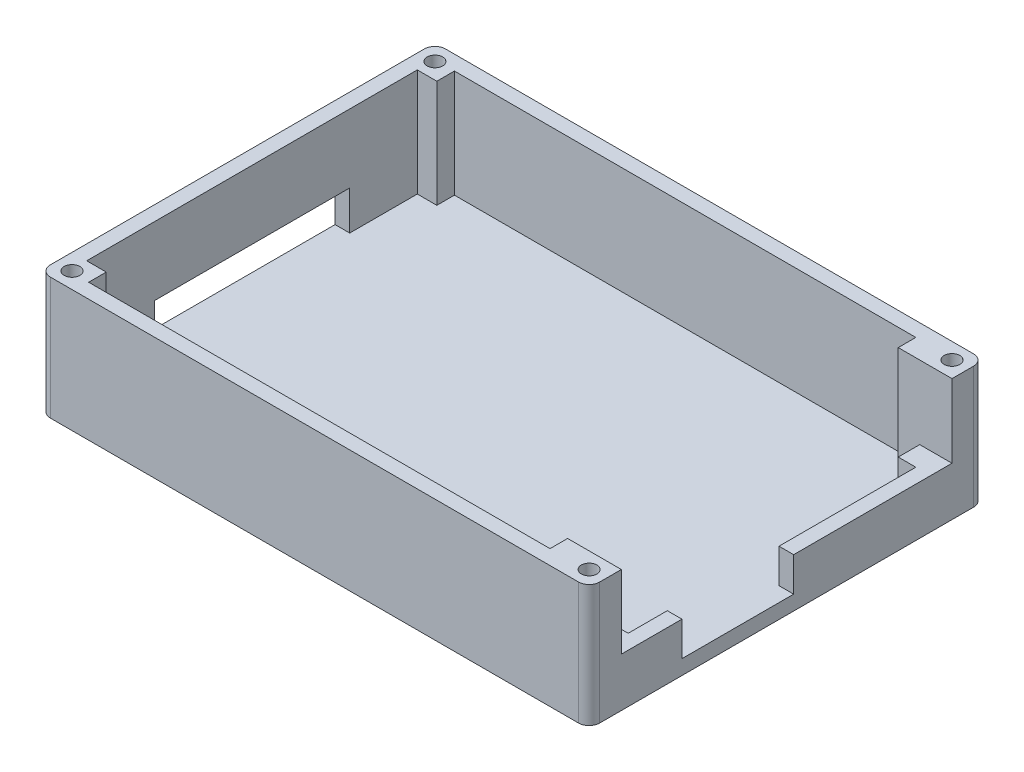
SolidWorks part; units mm, degrees
ref_plane "前视基准面" through (0, 0, 0) normal (0, 0, 1) x (1, 0, 0)
ref_plane "上视基准面" through (0, 0, 0) normal (0, 1, 0) x (1, 0, 0)
ref_plane "右视基准面" through (0, 0, 0) normal (1, 0, 0) x (0, 0, -1)
sketch "草图1" plane through (0, 0, 0) normal (0, 1, 0) x (1, 0, 0)
  line L1 (-38.8758, 22.2147) -> (17.3342, 22.2147)
  line L2 (-38.8758, 22.2147) -> (-38.8758, -18.2153)
  line L3 (-38.8758, -18.2153) -> (17.3342, -18.2153)
  line L4 (17.3342, 22.2147) -> (17.3342, -18.2153)
  line L5 (-10.7708, -18.2153) -> (-10.7708, 22.2147) construction
  line L6 (-38.8758, 1.9997) -> (17.3342, 1.9997) construction
  point P68 (-10.7708, 1.9997)
  dimension "D1" = 56.21
  dimension "D2" = 40.43
extrude "凸台-拉伸1" add sketch "草图1" along normal blind 1.5
sketch "草图2" plane through (0, 1.5, 0) normal (0, 1, 0) x (1, 0, 0)
  line L0 (-38.8758, -18.2153) -> (17.3342, -18.2153) construction
  line L1 (-38.8758, 22.2147) -> (-37.3758, 22.2147)
  line L2 (-38.8758, 22.2147) -> (-38.8758, -18.2153)
  line L3 (-38.8758, -18.2153) -> (-37.3758, -18.2153)
  line L4 (-37.3758, 22.2147) -> (-37.3758, -18.2153)
  line L5 (-38.1258, -18.2153) -> (-38.1258, 22.2147) construction
  line L6 (-38.8758, 1.9997) -> (-37.3758, 1.9997) construction
  line L7 (17.3342, -18.2153) -> (17.3342, 22.2147) construction
  line L12 (-37.3758, -18.2153) -> (17.3342, -18.2153)
  line L13 (-37.3758, -18.2153) -> (-37.3758, -16.7153)
  line L14 (-37.3758, -16.7153) -> (17.3342, -16.7153)
  line L15 (17.3342, -18.2153) -> (17.3342, -16.7153)
  line L16 (-10.0208, -16.7153) -> (-10.0208, -18.2153) construction
  line L17 (-37.3758, -17.4653) -> (17.3342, -17.4653) construction
  line L19 (-37.3758, 22.2147) -> (17.3342, 22.2147)
  line L20 (-37.3758, 22.2147) -> (-37.3758, 20.7147)
  line L21 (-37.3758, 20.7147) -> (17.3342, 20.7147)
  line L22 (17.3342, 22.2147) -> (17.3342, 20.7147)
  line L23 (-10.0208, 20.7147) -> (-10.0208, 22.2147) construction
  line L24 (-37.3758, 21.4647) -> (17.3342, 21.4647) construction
  point P152 (-38.1258, 1.9997)
  point P161 (-10.0208, 21.4647)
  point P193 (-10.0208, -17.4653)
  line M6 (-38.8758, 22.2147) -> (-38.8758, -18.2153)
  line M7 (-38.8758, -18.2153) -> (17.3342, -18.2153)
  line M8 (17.3342, -18.2153) -> (17.3342, 22.2147)
  line M9 (17.3342, 22.2147) -> (-38.8758, 22.2147)
  dimension "D1" = 1.5
  dimension "D2" = 1.5
  dimension "D3" = 1.5
extrude "凸台-拉伸2" add sketch "草图2" along normal blind 3.5 contours L4 M9 M6 M7 | L4 L21 M8 M9 | L14 L4 M7 M8
sketch "草图3" plane through (0, 1.5, 0) normal (0, 1, 0) x (1, 0, 0)
  line L1 (17.3342, -16.7153) -> (15.8342, -16.7153)
  line L2 (17.3342, -16.7153) -> (17.3342, -8.7153)
  line L3 (17.3342, -8.7153) -> (15.8342, -8.7153)
  line L4 (15.8342, -16.7153) -> (15.8342, -8.7153)
  line L5 (16.5842, -8.7153) -> (16.5842, -16.7153) construction
  line L6 (17.3342, -12.7153) -> (15.8342, -12.7153) construction
  line L7 (17.3342, 20.7147) -> (15.8342, 20.7147)
  line L8 (17.3342, 20.7147) -> (17.3342, 2.7147)
  line L9 (17.3342, 2.7147) -> (15.8342, 2.7147)
  line L10 (15.8342, 20.7147) -> (15.8342, 2.7147)
  line L11 (16.5842, 2.7147) -> (16.5842, 20.7147) construction
  line L12 (17.3342, 11.7147) -> (15.8342, 11.7147) construction
  point P108 (16.5842, 11.7147)
  point P172 (16.5842, -12.7153)
  dimension "D1" = 1.5
  dimension "D2" = 8
  dimension "D3" = 18
  dimension "D4" = 1.5
extrude "凸台-拉伸3" add sketch "草图3" along normal blind 3.5
sketch "草图4" plane through (0, 1.5, 0) normal (0, 1, 0) x (1, 0, 0)
  line L1 (15.8342, -16.7153) -> (14.0342, -16.7153)
  line L2 (15.8342, -16.7153) -> (15.8342, -12.7153)
  line L3 (15.8342, -12.7153) -> (14.0342, -12.7153)
  line L4 (14.0342, -16.7153) -> (14.0342, -12.7153)
  line L5 (14.9342, -12.7153) -> (14.9342, -16.7153) construction
  line L6 (15.8342, -14.7153) -> (14.0342, -14.7153) construction
  line L7 (14.0342, -16.7153) -> (11.8342, -16.7153)
  line L8 (14.0342, -16.7153) -> (14.0342, -14.9153)
  line L9 (14.0342, -14.9153) -> (11.8342, -14.9153)
  line L10 (11.8342, -16.7153) -> (11.8342, -14.9153)
  line L11 (12.9342, -14.9153) -> (12.9342, -16.7153) construction
  line L12 (14.0342, -15.8153) -> (11.8342, -15.8153) construction
  line L15 (15.8342, 20.7147) -> (15.8342, 16.7147)
  line L16 (15.8342, 20.7147) -> (14.0342, 20.7147)
  line L17 (14.0342, 20.7147) -> (11.8342, 20.7147)
  line L18 (11.8342, 20.7147) -> (11.8342, 18.9147)
  line L19 (14.0342, 18.9147) -> (11.8342, 18.9147)
  line L20 (14.0342, 20.7147) -> (14.0342, 16.7147)
  line L21 (15.8342, 16.7147) -> (14.0342, 16.7147)
  point P100 (14.9342, -14.7153)
  point P109 (12.9342, -15.8153)
  line M10 (15.8342, 2.7147) -> (15.8342, 20.7147)
  line M11 (15.8342, 20.7147) -> (-37.3758, 20.7147)
  line M13 (-37.3758, -16.7153) -> (15.8342, -16.7153)
  line M14 (15.8342, -16.7153) -> (15.8342, -8.7153)
  dimension "D1" = 1.8
  dimension "D2" = 4
  dimension "D3" = 2.2
  dimension "D4" = 1.8
extrude "凸台-拉伸4" add sketch "草图4" along normal blind 3.5 contours L20 L18 L19 M11 | L21 L20 M10 M11 | L4 L3 M13 M14 | L10 L4 L9 M13
sketch "草图5" plane through (0, 1.5, 0) normal (0, 1, 0) x (1, 0, 0)
  line L1 (-37.3758, 20.7147) -> (-35.3758, 20.7147)
  line L2 (-37.3758, 20.7147) -> (-37.3758, 18.9147)
  line L3 (-37.3758, 18.9147) -> (-35.3758, 18.9147)
  line L4 (-35.3758, 20.7147) -> (-35.3758, 18.9147)
  line L5 (-36.3758, 18.9147) -> (-36.3758, 20.7147) construction
  line L6 (-37.3758, 19.8147) -> (-35.3758, 19.8147) construction
  line L7 (-37.3758, -16.7153) -> (-35.3758, -16.7153)
  line L8 (-37.3758, -16.7153) -> (-37.3758, -14.9153)
  line L9 (-37.3758, -14.9153) -> (-35.3758, -14.9153)
  line L10 (-35.3758, -16.7153) -> (-35.3758, -14.9153)
  line L11 (-36.3758, -14.9153) -> (-36.3758, -16.7153) construction
  line L12 (-37.3758, -15.8153) -> (-35.3758, -15.8153) construction
  point P136 (-36.3758, -15.8153)
  point P184 (-36.3758, 19.8147)
  dimension "D1" = 2
  dimension "D2" = 1.8
  dimension "D3" = 2
  dimension "D4" = 1.8
extrude "凸台-拉伸5" add sketch "草图5" along normal blind 3.5
sketch "草图8" plane through (0, 5, 0) normal (0, 1, 0) x (1, 0, 0)
  line L0 (14.0342, -14.9153) -> (17.3342, -14.9153)
  line L1 (14.0342, 18.9147) -> (17.3342, 18.9147)
  line L24 (-37.3758, -14.9153) -> (-37.3758, 18.9147)
  line L25 (-37.3758, 18.9147) -> (-35.3758, 18.9147)
  line L26 (-35.3758, 18.9147) -> (-35.3758, 20.7147)
  line L27 (-35.3758, 20.7147) -> (11.8342, 20.7147)
  line L28 (11.8342, 20.7147) -> (11.8342, 18.9147)
  line L29 (11.8342, 18.9147) -> (14.0342, 18.9147)
  line L30 (14.0342, 18.9147) -> (14.0342, 16.7147)
  line L31 (14.0342, 16.7147) -> (15.8342, 16.7147)
  line L32 (15.8342, 16.7147) -> (15.8342, 2.7147)
  line L33 (15.8342, 2.7147) -> (17.3342, 2.7147)
  line L34 (17.3342, 2.7147) -> (17.3342, 22.2147)
  line L35 (17.3342, 22.2147) -> (-38.8758, 22.2147)
  line L36 (-38.8758, 22.2147) -> (-38.8758, -18.2153)
  line L37 (-38.8758, -18.2153) -> (17.3342, -18.2153)
  line L38 (17.3342, -18.2153) -> (17.3342, -8.7153)
  line L39 (17.3342, -8.7153) -> (15.8342, -8.7153)
  line L40 (15.8342, -8.7153) -> (15.8342, -12.7153)
  line L41 (15.8342, -12.7153) -> (14.0342, -12.7153)
  line L42 (14.0342, -12.7153) -> (14.0342, -14.9153)
  line L43 (14.0342, -14.9153) -> (11.8342, -14.9153)
  line L44 (11.8342, -14.9153) -> (11.8342, -16.7153)
  line L45 (11.8342, -16.7153) -> (-35.3758, -16.7153)
  line L46 (-35.3758, -16.7153) -> (-35.3758, -14.9153)
  line L47 (-35.3758, -14.9153) -> (-37.3758, -14.9153)
  line L48 (-37.3758, -14.9153) -> (-37.3758, 18.9147)
  line L49 (-37.3758, 18.9147) -> (-35.3758, 18.9147)
  line L50 (-35.3758, 18.9147) -> (-35.3758, 20.7147)
  line L51 (-35.3758, 20.7147) -> (11.8342, 20.7147)
  line L52 (11.8342, 20.7147) -> (11.8342, 18.9147)
  line L53 (11.8342, 18.9147) -> (14.0342, 18.9147)
  line L54 (14.0342, 18.9147) -> (14.0342, 16.7147)
  line L55 (14.0342, 16.7147) -> (15.8342, 16.7147)
  line L56 (15.8342, 16.7147) -> (15.8342, 2.7147)
  line L57 (15.8342, 2.7147) -> (17.3342, 2.7147)
  line L58 (17.3342, 2.7147) -> (17.3342, 22.2147)
  line L59 (17.3342, 22.2147) -> (-38.8758, 22.2147)
  line L60 (-38.8758, 22.2147) -> (-38.8758, -18.2153)
  line L61 (-38.8758, -18.2153) -> (17.3342, -18.2153)
  line L62 (17.3342, -18.2153) -> (17.3342, -8.7153)
  line L63 (17.3342, -8.7153) -> (15.8342, -8.7153)
  line L64 (15.8342, -8.7153) -> (15.8342, -12.7153)
  line L65 (15.8342, -12.7153) -> (14.0342, -12.7153)
  line L66 (14.0342, -12.7153) -> (14.0342, -14.9153)
  line L67 (14.0342, -14.9153) -> (11.8342, -14.9153)
  line L68 (11.8342, -14.9153) -> (11.8342, -16.7153)
  line L69 (11.8342, -16.7153) -> (-35.3758, -16.7153)
  line L70 (-35.3758, -16.7153) -> (-35.3758, -14.9153)
  line L71 (-35.3758, -14.9153) -> (-37.3758, -14.9153)
  line M25 (-37.3758, -14.9153) -> (-37.3758, 18.9147)
  line M26 (-37.3758, 18.9147) -> (-35.3758, 18.9147)
  line M27 (-35.3758, 18.9147) -> (-35.3758, 20.7147)
  line M28 (-35.3758, 20.7147) -> (11.8342, 20.7147)
  line M29 (11.8342, 20.7147) -> (11.8342, 18.9147)
  line M30 (11.8342, 18.9147) -> (14.0342, 18.9147)
  line M35 (17.3342, 2.7147) -> (17.3342, 22.2147)
  line M36 (17.3342, 22.2147) -> (-38.8758, 22.2147)
  line M37 (-38.8758, 22.2147) -> (-38.8758, -18.2153)
  line M38 (-38.8758, -18.2153) -> (17.3342, -18.2153)
  line M39 (17.3342, -18.2153) -> (17.3342, -8.7153)
  line M44 (14.0342, -14.9153) -> (11.8342, -14.9153)
  line M45 (11.8342, -14.9153) -> (11.8342, -16.7153)
  line M46 (11.8342, -16.7153) -> (-35.3758, -16.7153)
  line M47 (-35.3758, -16.7153) -> (-35.3758, -14.9153)
  line M48 (-35.3758, -14.9153) -> (-37.3758, -14.9153)
  dimension "D1" = 0
extrude "凸台-拉伸9" add sketch "草图8" along normal blind 7.5 contours L1 L0 M30 M35 M36 M37 M38 M39 M44 M45 M46 M47 M48 M25 M26 M27 M28 M29
sketch "草图9" plane through (0, 12.5, 0) normal (0, 1, 0) x (1, 0, 0)
  line L0 (17.3342, 22.2147) -> (17.3342, 20.5647)
  line L1 (17.3342, 18.9147) -> (17.3342, 22.2147) construction
  line L2 (17.3342, 20.5647) -> (15.6842, 20.5647)
  line L3 (17.3342, -18.2153) -> (17.3342, -16.5653)
  line L4 (17.3342, -18.2153) -> (17.3342, -14.9153) construction
  line L5 (17.3342, -16.5653) -> (15.6842, -16.5653)
  line L6 (-38.8758, 22.2147) -> (-38.8758, 20.5647)
  line L7 (-38.8758, 22.2147) -> (-38.8758, -18.2153) construction
  line L8 (-38.8758, 20.5647) -> (-37.2258, 20.5647)
  line L9 (-38.8758, -18.2153) -> (-38.8758, -16.5653)
  line L10 (-38.8758, -16.5653) -> (-37.2258, -16.5653)
  circle A0 centre (15.6842, 20.5647) radius 0.8
  circle A1 centre (15.6842, -16.5653) radius 0.8
  circle A2 centre (-37.2258, 20.5647) radius 0.8
  circle A3 centre (-37.2258, -16.5653) radius 0.8
  dimension "D2" = 1.6
  dimension "D4" = 1.6
  dimension "D6" = 1.6
  dimension "D7" = 1.6
  dimension "D1" = 1.65
  dimension "D3" = 1.65
  dimension "D5" = 1.65
extrude "切除-拉伸1" cut sketch "草图9" against normal blind 7.5
sketch "草图11" plane through (-37.3758, 0, 0) normal (1, 0, 0) x (0, 0, -1)
  line L0 (18.9147, 1.5) -> (-14.9153, 1.5) construction
  line L1 (1.9997, 1.5) -> (11.9997, 1.5)
  line L2 (1.9997, 1.5) -> (1.9997, 5.5)
  line L3 (1.9997, 5.5) -> (11.9997, 5.5)
  line L4 (11.9997, 1.5) -> (11.9997, 5.5)
  line L5 (6.9997, 5.5) -> (6.9997, 1.5) construction
  line L6 (1.9997, 3.5) -> (11.9997, 3.5) construction
  line L8 (1.9997, 1.5) -> (-8.0003, 1.5)
  line L9 (1.9997, 1.5) -> (1.9997, 5.5)
  line L10 (1.9997, 5.5) -> (-8.0003, 5.5)
  line L11 (-8.0003, 1.5) -> (-8.0003, 5.5)
  line L12 (-3.0003, 5.5) -> (-3.0003, 1.5) construction
  line L13 (1.9997, 3.5) -> (-8.0003, 3.5) construction
  point P192 (6.9997, 3.5)
  point P313 (-3.0003, 3.5)
  line M17 (-14.9153, 1.5) -> (18.9147, 1.5)
  dimension "D1" = 4
  dimension "D2" = 10
  dimension "D3" = 10
extrude "切除-拉伸2" cut sketch "草图11" against normal blind 7.5 contours L4 L3 L2 M17 | L11 L2 L10 M17
sketch "草图14" plane through (0, 12.5, 0) normal (0, 1, 0) x (1, 0, 0)
  line L0 (-38.8758, 1.9997) -> (-37.3758, 1.9997)
  line L1 (17.3342, 22.2147) -> (-38.8758, 22.2147) construction
  line L2 (-38.8758, 22.2147) -> (-38.8758, -18.2153) construction
  line L3 (-38.8758, 21.1304) -> (-38.8758, 22.2147)
  line L4 (-38.8758, 22.2147) -> (-37.7915, 22.2147)
  line L5 (-37.3758, -14.9153) -> (-37.3758, 18.9147) construction
  line L6 (-38.8758, -17.131) -> (-38.8758, -18.2153)
  line L7 (-38.8758, -18.2153) -> (-37.7915, -18.2153)
  line L8 (-10.7708, 22.2147) -> (-10.7708, 20.7147)
  line L9 (-35.3758, 20.7147) -> (11.8342, 20.7147) construction
  line L10 (17.3342, -18.2153) -> (16.2499, -18.2153)
  line L11 (17.3342, -17.131) -> (17.3342, -18.2153)
  line L12 (17.3342, 21.1304) -> (17.3342, 22.2147)
  line L13 (17.3342, 22.2147) -> (16.2499, 22.2147)
  arc A0 (-37.7915, 22.2147) -> (-38.8758, 21.1304) centre (-37.7915, 21.1304) ccw
  circle A1 centre (-37.2258, 20.5647) radius 0.8 construction
  arc A2 (-37.7915, -18.2153) -> (-38.8758, -17.131) centre (-37.7915, -17.131) cw
  arc A3 (16.2499, -18.2153) -> (17.3342, -17.131) centre (16.2499, -17.131) ccw
  arc A4 (16.2499, 22.2147) -> (17.3342, 21.1304) centre (16.2499, 21.1304) cw
  line M14 (17.3342, 18.9147) -> (17.3342, 22.2147)
  line M15 (17.3342, 22.2147) -> (-38.8758, 22.2147)
  line M16 (-38.8758, 22.2147) -> (-38.8758, -18.2153)
  line M17 (-38.8758, -18.2153) -> (17.3342, -18.2153)
  line M18 (17.3342, -18.2153) -> (17.3342, -14.9153)
extrude "切除-拉伸3" cut sketch "草图14" against normal blind 15 contours A0 M15 M16 | A2 M17 M16 | A3 M17 M18 | A4 M15 M14
